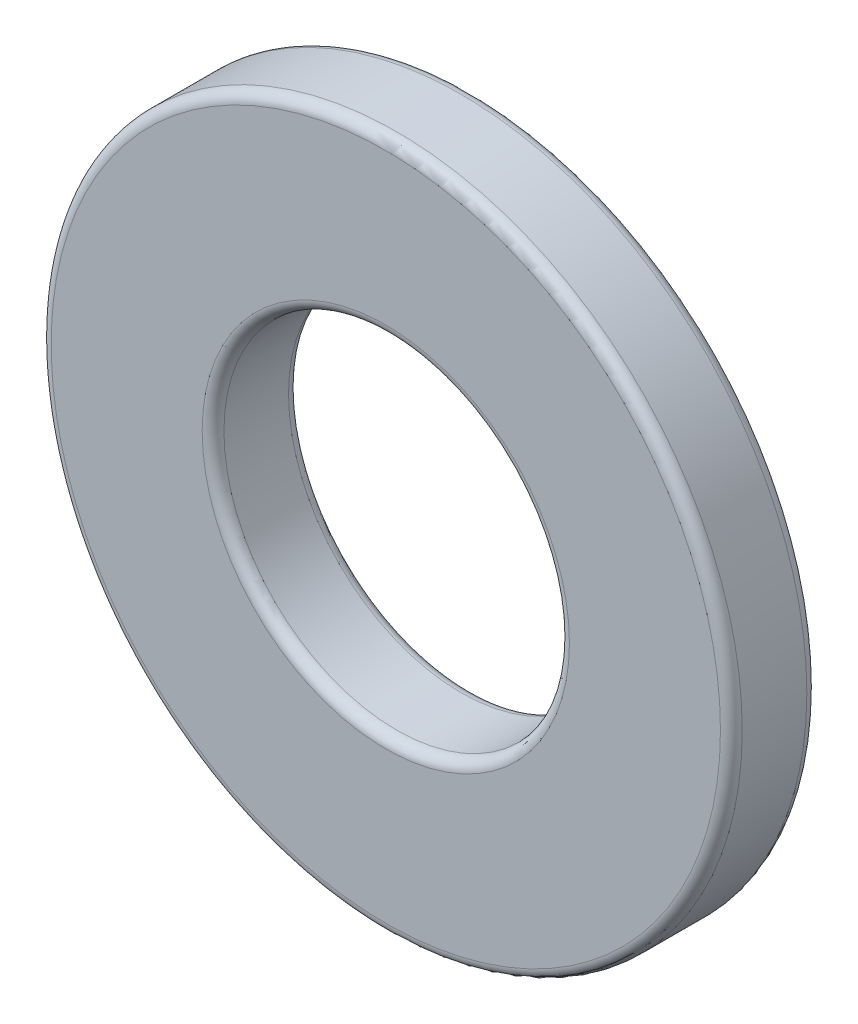
SolidWorks part; units mm, degrees
ref_plane "Front Plane" through (0, 0, 0) normal (0, 0, 1) x (1, 0, 0)
ref_plane "Top Plane" through (0, 0, 0) normal (0, 1, 0) x (1, 0, 0)
ref_plane "Right Plane" through (0, 0, 0) normal (1, 0, 0) x (0, 0, -1)
sketch "Sketch1" plane through (0, 0, 0) normal (0, 0, 1) x (1, 0, 0)
  circle A0 centre (68.3982, 3.2144) radius 6.35
  dimension "D1" = 12.7
extrude "Boss-Extrude1" add sketch "Sketch1" along normal blind 1.5875
sketch "Sketch2" plane through (0, 0, 0) normal (0, 0, -1) x (-1, 0, 0)
  circle A0 centre (-68.3982, 3.2144) radius 3.175
  dimension "D1" = 6.35
extrude "Cut-Extrude1" cut sketch "Sketch2" against normal through all
fillet "Fillet1" radius 0.2 4 edges at (74.7482, 3.2144, 0) (65.2232, 3.2144, 0) (74.7482, 3.2144, 1.5875) (65.2232, 3.2144, 1.5875)
